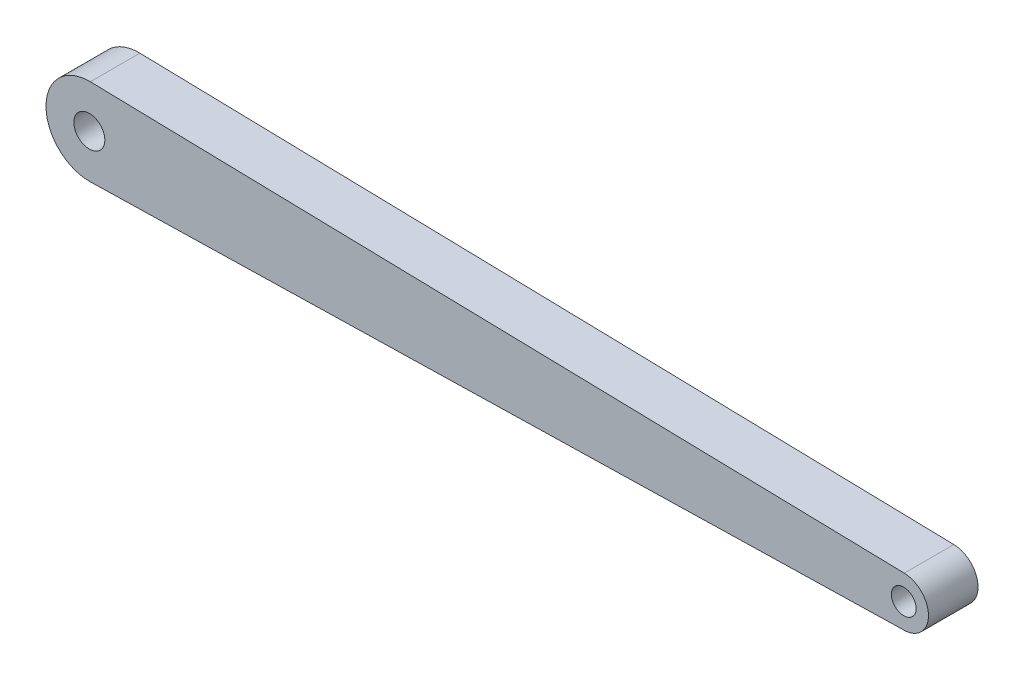
SolidWorks part; units mm, degrees
ref_plane "Front Plane" through (0, 0, 0) normal (0, 0, 1) x (1, 0, 0)
ref_plane "Top Plane" through (0, 0, 0) normal (0, 1, 0) x (1, 0, 0)
ref_plane "Right Plane" through (0, 0, 0) normal (1, 0, 0) x (0, 0, -1)
sketch "Sketch1" plane through (0, 0, 0) normal (0, 0, 1) x (1, 0, 0)
  line L0 (0, 0) -> (-1315, 0) construction
  line L1 (-1313.403, 69.9818) -> (0.9125, 39.9896)
  line L2 (-1313.403, -69.9818) -> (0.9125, -39.9896)
  circle A0 centre (0, 0) radius 20
  circle A1 centre (-1315, 0) radius 25
  arc A2 (-1313.403, 69.9818) -> (-1313.403, -69.9818) centre (-1315, 0) ccw
  arc A3 (0.9125, 39.9896) -> (0.9125, -39.9896) centre (0, 0) cw
  point P9 (-1331.7627, -96.1187)
  dimension "D2" = 40
  dimension "D3" = 50
  dimension "D4" = 70
  dimension "D5" = 40
  dimension "D1" = 1315
extrude "Boss-Extrude1" add sketch "Sketch1" along normal mid plane 80
